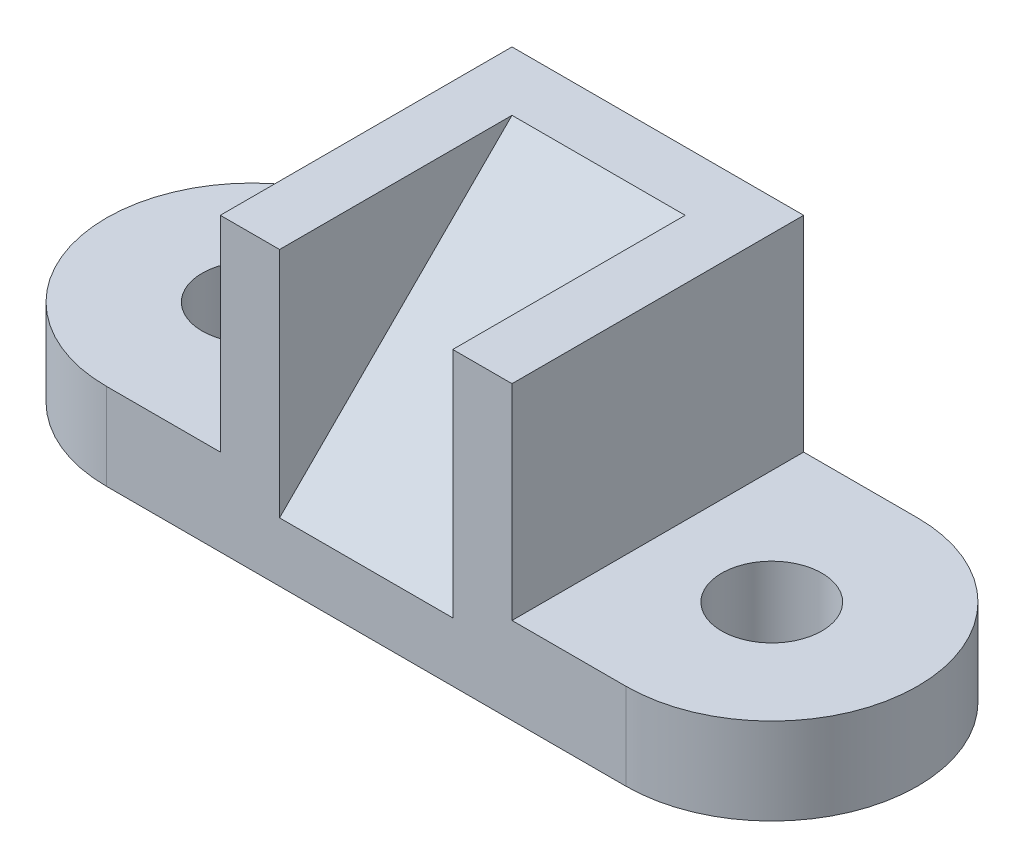
SolidWorks part; units mm, degrees
ref_plane "Front Plane" through (0, 0, 0) normal (0, 0, 1) x (1, 0, 0)
ref_plane "Top Plane" through (0, 0, 0) normal (0, 1, 0) x (1, 0, 0)
ref_plane "Right Plane" through (0, 0, 0) normal (1, 0, 0) x (0, 0, -1)
sketch "Sketch1" plane through (0, 0, 0) normal (0, 1, 0) x (1, 0, 0)
  line L0 (57, 0) -> (-57, 0) construction
  line L1 (57, -32) -> (-57, -32)
  line L2 (57, 32) -> (-57, 32)
  arc A0 (57, -32) -> (57, 32) centre (57, 0) ccw
  arc A1 (-57, 32) -> (-57, -32) centre (-57, 0) ccw
  circle A2 centre (-57, 0) radius 11
  circle A3 centre (57, 0) radius 11
  point P2 (0, 0)
  dimension "D2" = 32
  dimension "D3" = 22
  dimension "D4" = 22
  dimension "D1" = 114
extrude "Boss-Extrude1" add sketch "Sketch1" along normal blind 19
sketch "Sketch2" plane through (0, 19, 0) normal (0, 1, 0) x (1, 0, 0)
  line L0 (-57, -32) -> (57, -32) construction
  line L1 (32, 32) -> (-32, 32)
  line L2 (32, 32) -> (32, -32)
  line L3 (32, -32) -> (-32, -32)
  line L4 (-32, 32) -> (-32, -32)
  line L5 (32, 32) -> (-32, -32) construction
  line L6 (32, -32) -> (-32, 32) construction
  point P0 (0, 0)
  point P8 (-32, 0)
  dimension "D1" = 64
extrude "Boss-Extrude2" add sketch "Sketch2" along normal blind 45
sketch "Sketch5" plane through (-32, 0, 0) normal (-1, 0, 0) x (0, 0, 1)
  line L0 (-19, 64) -> (32, 13)
  line L1 (-32, 64) -> (32, 64) construction
  line L2 (32, 19) -> (32, 0) construction
  line L3 (32, 13) -> (32, 64)
  line L4 (32, 64) -> (-19, 64)
  dimension "D1" = 13
  dimension "D2" = 13
extrude "Cut-Extrude1" cut sketch "Sketch5" against normal blind 38 from offset 13
